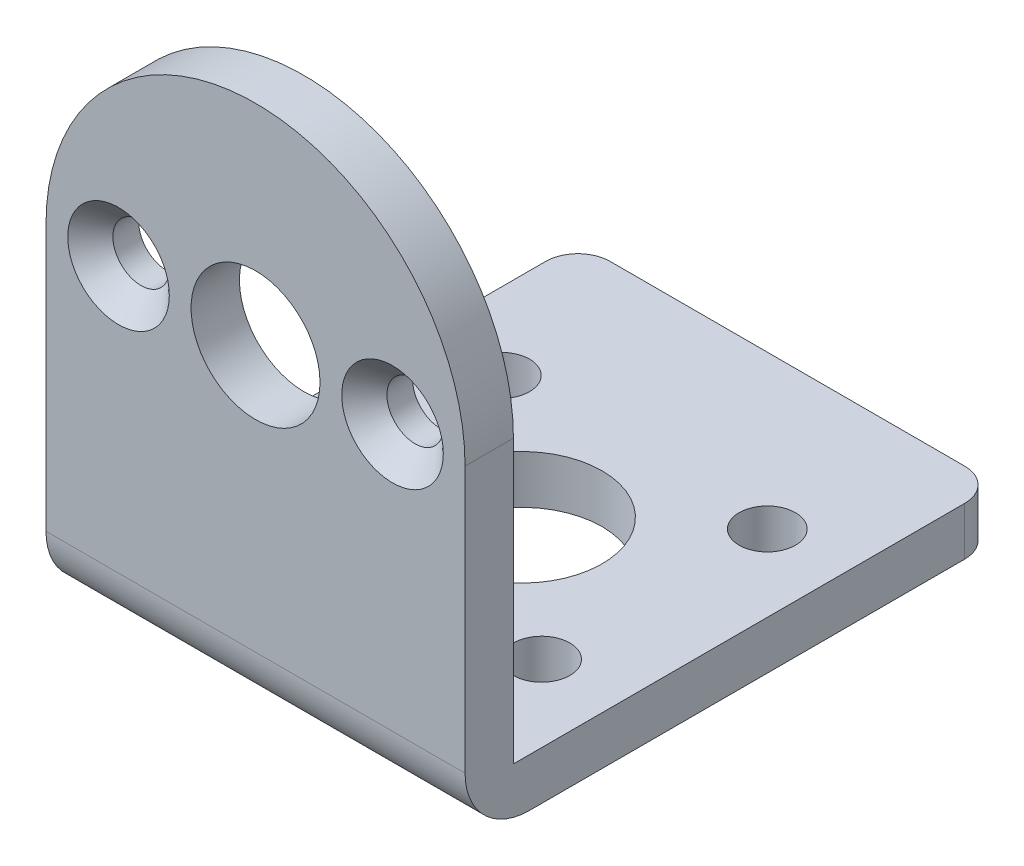
SolidWorks part; units mm, degrees
ref_plane "前视基准面" through (0, 0, 0) normal (0, 0, 1) x (1, 0, 0)
ref_plane "上视基准面" through (0, 0, 0) normal (0, 1, 0) x (1, 0, 0)
ref_plane "右视基准面" through (0, 0, 0) normal (1, 0, 0) x (0, 0, -1)
sketch "草图2" plane through (0, 0, 0) normal (0, 1, 0) x (1, 0, 0)
  line L0 (0, 0) -> (-728.5055, 0) construction
  line L1 (-330.2, -419.1) -> (330.2, -419.1)
  line L2 (-330.2, -419.1) -> (-330.2, 368.3)
  line L3 (-279.4, 419.1) -> (279.4, 419.1)
  line L4 (330.2, -419.1) -> (330.2, 368.3)
  line L5 (-330.2, -342.9) -> (330.2, -342.9)
  line L7 (0, 0) -> (0, -583.6418) construction
  circle A0 centre (0, 0) radius 127
  circle A2 centre (-209.55, 177.8) radius 44.45
  circle A3 centre (-209.55, -177.8) radius 44.45
  circle A4 centre (209.55, -177.8) radius 44.45
  circle A5 centre (209.55, 177.8) radius 44.45
  arc A6 (330.2, 368.3) -> (279.4, 419.1) centre (279.4, 368.3) ccw
  arc A7 (-279.4, 419.1) -> (-330.2, 368.3) centre (-279.4, 368.3) ccw
  point P0 (0, 0)
  point P24 (330.2, 419.1)
  point P27 (-330.2, 419.1)
  dimension "D3" = 254
  dimension "D4" = 88.9
  dimension "D9" = 50.8
  dimension "D1" = 838.2
  dimension "D2" = 660.4
  dimension "D5" = 177.8
  dimension "D6" = 355.6
  dimension "D7" = 419.1
  dimension "D8" = 76.2
  dimension "D10" = 419.1
  dimension "D11" = 330.2
extrude "凸台-拉伸1" add sketch "草图2" along normal blind 76.2 contours L3 A7 L2 L5 L4 A6 A5 A0 A2 A3 A4
sketch "草图4" plane through (0, 0, 0) normal (0, 1, 0) x (1, 0, 0)
  line L0 (-330.2, -419.1) -> (-330.2, 368.3) construction
  line L1 (-330.2, -419.1) -> (-330.2, 368.3)
  line L2 (-330.2, -342.9) -> (330.2, -342.9) construction
  line L3 (-330.2, -342.9) -> (330.2, -342.9)
  line L4 (-330.2, -419.1) -> (330.2, -419.1) construction
  line L5 (-330.2, -419.1) -> (330.2, -419.1)
  line L6 (330.2, -419.1) -> (330.2, 368.3) construction
  line L7 (330.2, -419.1) -> (330.2, 368.3)
extrude "凸台-拉伸2" add sketch "草图4" along normal blind 850.9 contours L5 L7 L3 L1
fillet "圆角2" radius 101.6 1 edges at (0, 0, 419.1)
sketch "草图5" plane through (0, 0, 419.1) normal (0, 0, 1) x (1, 0, 0)
  line L0 (0, 0) -> (0, 836.24) construction
  line L1 (-279.4, 0) -> (279.4, 0) construction
  line L2 (0, 520.7) -> (-715.8572, 520.7) construction
  line L3 (330.2, 850.9) -> (330.2, 101.6) construction
  line L4 (-330.2, 850.9) -> (330.2, 850.9) construction
  line L5 (-330.2, 850.9) -> (-330.2, 101.6) construction
  line L6 (330.2, 850.9) -> (330.2, 101.6)
  line L7 (-330.2, 850.9) -> (330.2, 850.9)
  line L8 (-330.2, 850.9) -> (-330.2, 101.6)
  circle A0 centre (0, 520.7) radius 101.6
  circle A1 centre (0, 520.7) radius 330.2
  circle A2 centre (-215.9, 520.7) radius 44.45
  circle A3 centre (215.9, 520.7) radius 44.45
  point P1 (0, 520.7)
  line M6 (-330.2, 850.9) -> (-330.2, 101.6)
  line M9 (330.2, 850.9) -> (-330.2, 850.9)
  dimension "D2" = 660.4
  dimension "D3" = 203.2
  dimension "D4" = 88.9
  dimension "D1" = 520.7
  dimension "D5" = 215.9
extrude "切除-拉伸1" cut sketch "草图5" against normal blind 850.9 contours A1 L7 M6 | A1 L6 M9 | A3 | A2 | A0
sketch "草图7" plane through (0, 0, 419.1) normal (0, 0, 1) x (1, 0, 0)
  point P0 (-215.9, 520.7)
  point P1 (215.9, 520.7)
  point P5 (-215.9, 520.7)
  point P7 (215.9, 520.7)
  point P11 (-215.9, 520.7)
  point P13 (-215.9, 520.7)
  point P15 (-215.9, 520.7)
scale "缩放比例1" scale about centroid uniform scaling yes scale factor 0.03937
sketch "草图9" plane through (0, 0, 183.7899) normal (0, 0, 1) x (1, 0, 0)
  point P0 (-8.5, 234.1135)
  point P1 (8.5, 234.1135)
hole_wizard "M6 内六角花形半沉头螺钉的锥形沉头孔3" positions "草图9" profile "草图10" countersink size "M6" standard "GB"
sketch "草图10" plane through (-8.5, 234.1135, 183.7899) normal (1, 0, 0) x (0, -1, 0)
  line L0 (0, 0) -> (0, 17.5615)
  line L1 (0, 17.5615) -> (1.75, 16.51)
  line L2 (1.75, 16.51) -> (1.75, 1.4)
  line L3 (1.75, 1.4) -> (3.15, 0)
  line L5 (3.15, 0) -> (0, 0)
  line L6 (-1.75, 1.4) -> (-3.15, 0) construction
  line L10 (0, 17.5615) -> (-1.75, 16.51) construction
  line L11 (0, -6.35) -> (0, 107.95) construction
  dimension "孔直径" = 3.5
  dimension "孔深度" = 16.51
  dimension "近端锥形沉头孔直径" = 6.3
  dimension "近端锥形沉头孔角度" = 90
  dimension "导头角度" = 118
